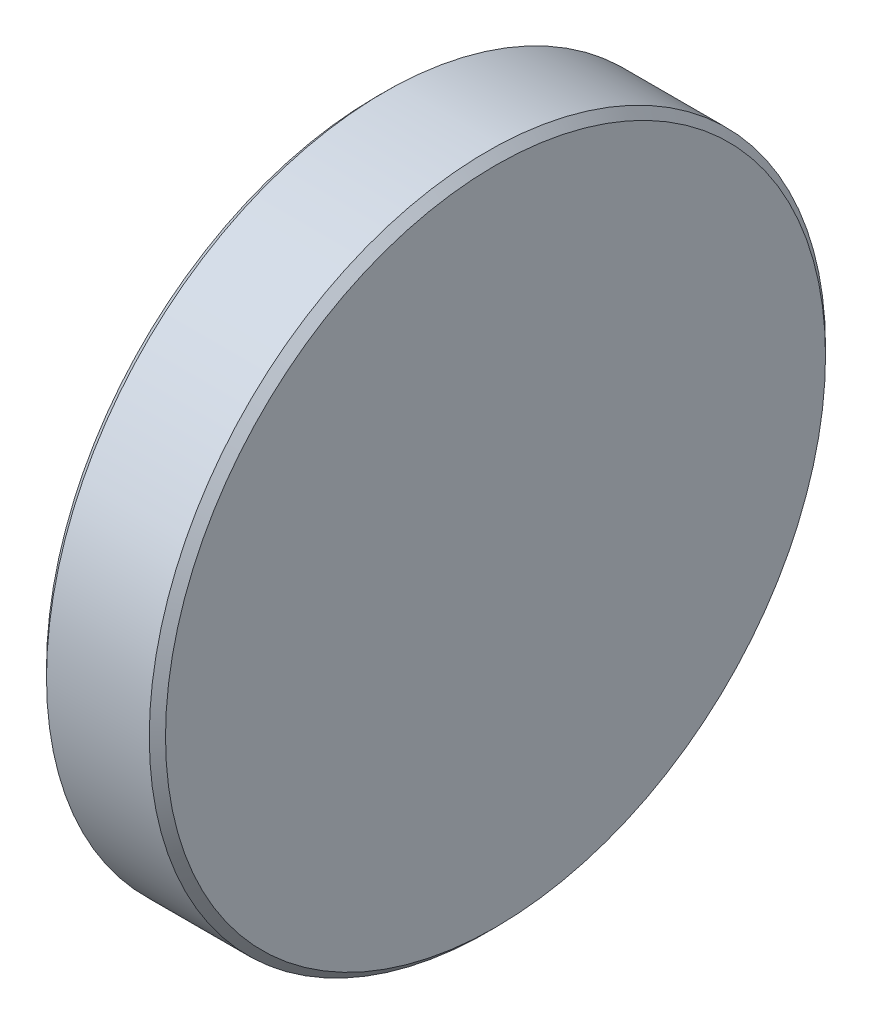
SolidWorks part; units mm, degrees
ref_plane "Front Plane" through (0, 0, 0) normal (1, 0, 0) x (0, 1, 0)
ref_plane "Top Plane" through (0, 0, 0) normal (0, 0, 1) x (0, 1, 0)
ref_plane "Right Plane" through (0, 0, 0) normal (0, 1, 0) x (-1, 0, 0)
sketch "Sketch1" plane through (0, 0, 0) normal (1, 0, 0) x (0, 1, 0)
  circle A0 centre (0, 0) radius 63.5
extrude "Boss-Extrude1" add sketch "Sketch1" along normal blind 22.352
sketch "Sketch2" plane through (0, 0, 0) normal (1, 0, 0) x (0, 1, 0)
  circle A0 centre (63.5, 63.5) radius 19.05
chamfer "Chamfer1" distance 1.524 angle 45 2 edges at (22.352, 0, -63.5) (0, 0, -63.5)
